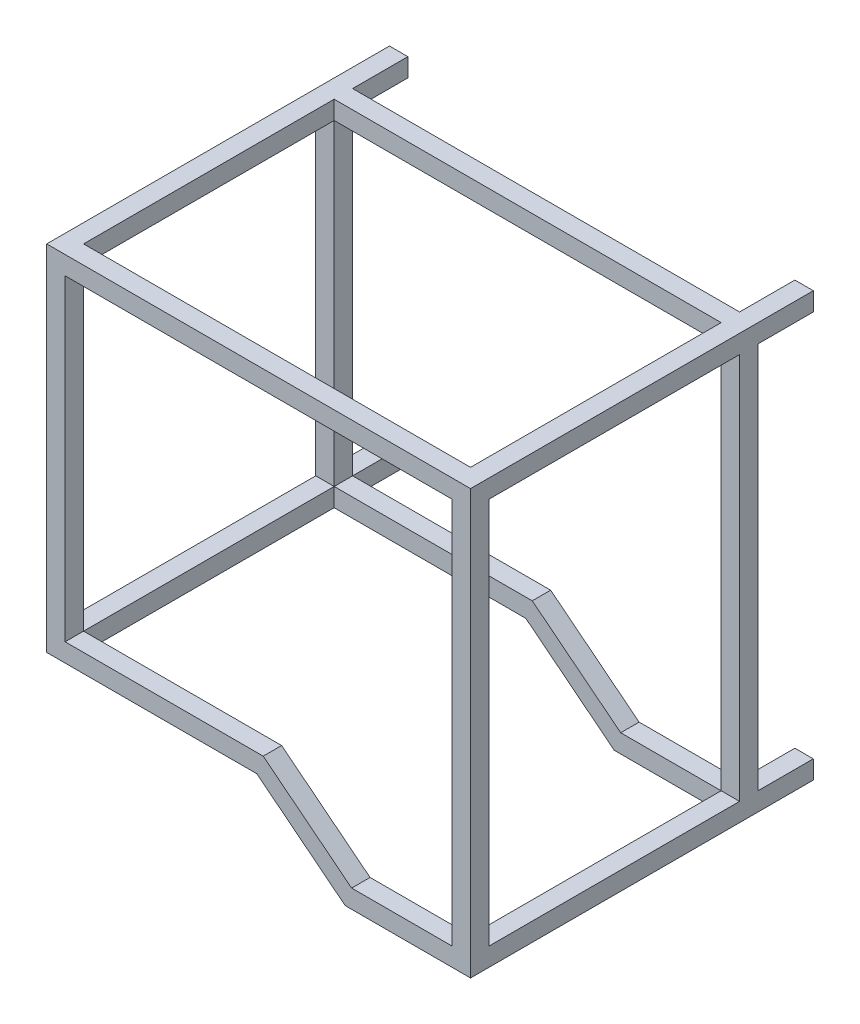
SolidWorks part; units mm, degrees
ref_plane "Piano frontale" through (0, 0, 0) normal (0, 0, 1) x (1, 0, 0)
ref_plane "Piano superiore" through (0, 0, 0) normal (0, 1, 0) x (1, 0, 0)
ref_plane "Piano destro" through (0, 0, 0) normal (1, 0, 0) x (0, 0, -1)
sketch "Schizzo1" plane through (0, 0, 0) normal (0, 0, 1) x (1, 0, 0)
  line L0 (0, 0) -> (1150, 0)
  line L1 (1150, 0) -> (1150, -1150)
  line L2 (1150, -1150) -> (810, -1150)
  line L3 (810, -1150) -> (570, -960)
  line L4 (570, -960) -> (0, -960)
  line L5 (0, -960) -> (0, 0)
  line L6 (50, -50) -> (1100, -50)
  line L7 (1100, -50) -> (1100, -1100)
  line L8 (1100, -1100) -> (827.3959, -1100)
  line L9 (827.3959, -1100) -> (587.3959, -910)
  line L10 (587.3959, -910) -> (50, -910)
  line L11 (50, -910) -> (50, -50)
  dimension "D1" = 1150
  dimension "D2" = 1150
  dimension "D3" = 340
  dimension "D4" = 240
  dimension "D5" = 960
  dimension "D6" = 50
extrude "Estrusione-Estrusione1" add sketch "Schizzo1" along normal blind 50 contours L5 L0 L1 L2 L3 L4 | L6 L7 L8 L9 L10 L11
ref_plane "Piano1" through (0, 0, 780) normal (0, 0, -1) x (-1, 0, 0)
sketch "Schizzo4" plane through (0, 0, 780) normal (0, 0, -1) x (-1, 0, 0)
  line L0 (-50, -50) -> (-1100, -50) construction
  line L1 (-50, -910) -> (-50, -50) construction
  line L2 (-587.3959, -910) -> (-50, -910) construction
  line L3 (-827.3959, -1100) -> (-587.3959, -910) construction
  line L4 (-1100, -50) -> (-1100, -1100) construction
  line L5 (-1100, -1100) -> (-827.3959, -1100) construction
  line L6 (-1150, -1150) -> (-810, -1150) construction
  line L7 (-810, -1150) -> (-570, -960) construction
  line L8 (-570, -960) -> (0, -960) construction
  line L9 (0, -960) -> (0, 0) construction
  line L10 (0, 0) -> (-1150, 0) construction
  line L11 (-1150, 0) -> (-1150, -1150) construction
  line L12 (-50, -50) -> (-1100, -50)
  line L13 (-50, -910) -> (-50, -50)
  line L14 (-587.3959, -910) -> (-50, -910)
  line L15 (-827.3959, -1100) -> (-587.3959, -910)
  line L16 (-1100, -50) -> (-1100, -1100)
  line L17 (-1100, -1100) -> (-827.3959, -1100)
  line L18 (-1150, -1150) -> (-810, -1150)
  line L19 (-810, -1150) -> (-570, -960)
  line L20 (-570, -960) -> (0, -960)
  line L21 (0, -960) -> (0, 0)
  line L22 (0, 0) -> (-1150, 0)
  line L23 (-1150, 0) -> (-1150, -1150)
extrude "Estrusione-Estrusione4" add sketch "Schizzo4" along normal blind 50 separate body
sketch "Schizzo5" plane through (0, 0, 730) normal (0, 0, -1) x (-1, 0, 0)
  line L1 (-1150, 0) -> (-1100, 0)
  line L2 (-1150, 0) -> (-1150, -50)
  line L3 (-1150, -50) -> (-1100, -50)
  line L4 (-1100, 0) -> (-1100, -50)
  line L5 (-50, -50) -> (0, -50)
  line L6 (-50, -50) -> (-50, 0)
  line L7 (-50, 0) -> (0, 0)
  line L8 (0, -50) -> (0, 0)
  line L9 (0, -960) -> (-50, -960)
  line L10 (0, -960) -> (0, -910)
  line L11 (0, -910) -> (-50, -910)
  line L12 (-50, -960) -> (-50, -910)
  line L13 (-1150, -1150) -> (-1100, -1150)
  line L14 (-1150, -1150) -> (-1150, -1100)
  line L15 (-1150, -1100) -> (-1100, -1100)
  line L16 (-1100, -1150) -> (-1100, -1100)
extrude "Estrusione-Estrusione5" add sketch "Schizzo5" along normal up to surface (680 mm away) up to face at (619.132, -686.6667, 50)
sketch "Schizzo6" plane through (0, 0, 0) normal (0, 0, -1) x (-1, 0, 0)
  line L0 (-50, -50) -> (-1100, -50) construction
  line L1 (0, -960) -> (-50, -960)
  line L2 (0, -960) -> (0, -910)
  line L3 (0, -910) -> (-50, -910)
  line L4 (-50, -960) -> (-50, -910)
  line L5 (-1150, -1150) -> (-1100, -1150)
  line L6 (-1150, -1150) -> (-1150, -1100)
  line L7 (-1150, -1100) -> (-1100, -1100)
  line L8 (-1100, -1150) -> (-1100, -1100)
  line L9 (-1100, -50) -> (-1150, -50)
  line L10 (-1100, -50) -> (-1100, 0)
  line L11 (-1100, 0) -> (-1150, 0)
  line L12 (-1150, -50) -> (-1150, 0)
  line L13 (0, 0) -> (-50, 0)
  line L14 (0, 0) -> (0, -50)
  line L15 (0, -50) -> (-50, -50)
  line L16 (-50, 0) -> (-50, -50)
extrude "Estrusione-Estrusione6" add sketch "Schizzo6" along normal blind 150
